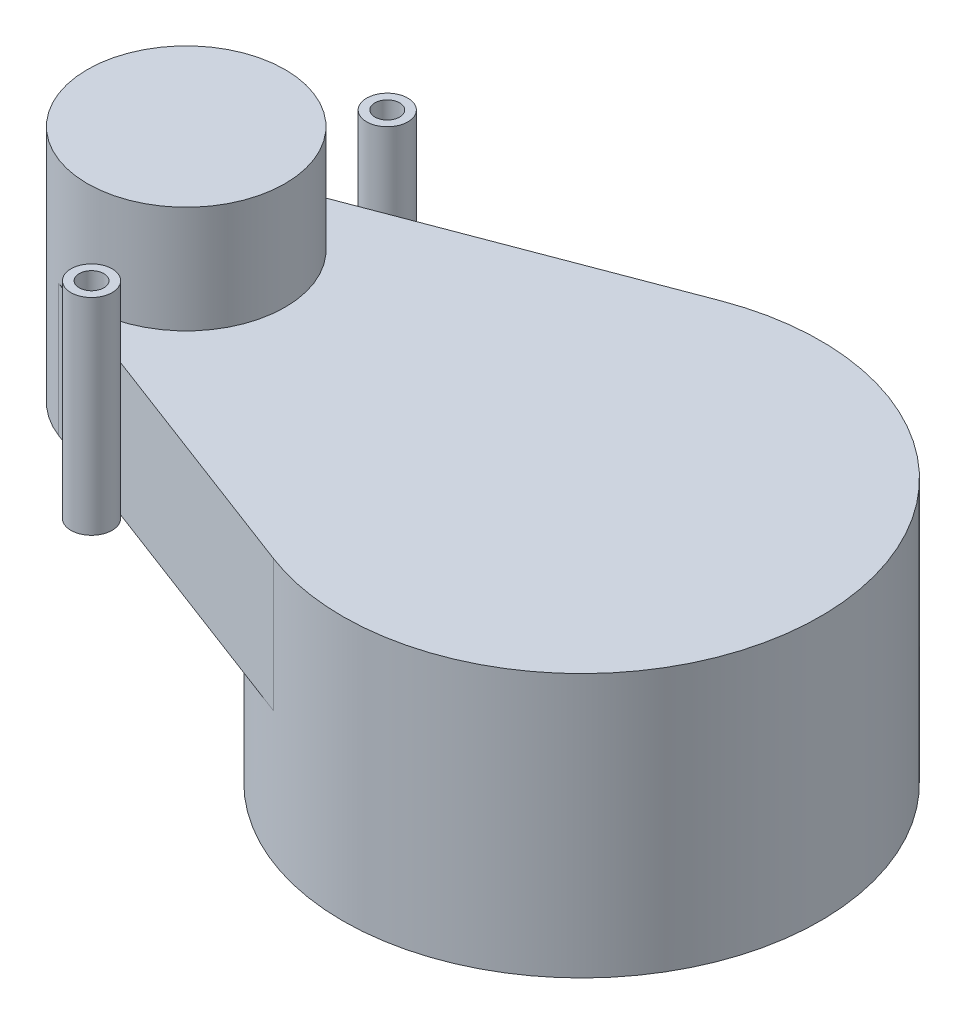
SolidWorks part; units mm, degrees
ref_plane "前视基准面" through (0, 0, 0) normal (0, 0, 1) x (1, 0, 0)
ref_plane "上视基准面" through (0, 0, 0) normal (0, 1, 0) x (1, 0, 0)
ref_plane "右视基准面" through (0, 0, 0) normal (1, 0, 0) x (0, 0, -1)
other "Configuration Table"
sketch "草图1" plane through (0, 0, 0) normal (0, 1, 0) x (1, 0, 0)
  circle A0 centre (0, 0) radius 29
  dimension "D1" = 58
extrude "凸台-拉伸1" add sketch "草图1" against normal blind 16 contours A0
sketch "草图2" plane through (0, 0, 0) normal (0, 1, 0) x (1, 0, 0)
  line L0 (-10.2708, 27.1203) -> (-52.25, 11.2222)
  line L1 (-10.2708, -27.1203) -> (-52.25, -11.2222)
  line L2 (-117.9064, 0) -> (30.9422, 0) construction
  circle A1 centre (0, 0) radius 29
  arc A2 (-10.2708, -27.1203) -> (-10.2708, 27.1203) centre (0, 0) ccw
  arc A3 (-52.25, 11.2222) -> (-52.25, -11.2222) centre (-48, 0) ccw
  circle A4 centre (0, 0) radius 29 construction
  dimension "D2" = 12
  dimension "D3" = 48
  dimension "D1" = 0
extrude "凸台-拉伸2" add sketch "草图2" along normal blind 16
sketch "草图3" plane through (0, 16, 0) normal (0, 1, 0) x (1, 0, 0)
  line L2 (-10.2708, 27.1203) -> (-52.25, 11.2222)
  line L3 (-52.25, -11.2222) -> (-10.2708, -27.1203)
  line L4 (-10.2708, 27.1203) -> (-52.25, 11.2222)
  line L5 (-52.25, -11.2222) -> (-10.2708, -27.1203)
  circle A0 centre (-48, 0) radius 12
  arc A2 (-10.2708, -27.1203) -> (-10.2708, 27.1203) centre (0, 0) ccw
  arc A3 (-52.25, 11.2222) -> (-52.25, -11.2222) centre (-48, 0) ccw
  arc A4 (-10.2708, -27.1203) -> (-10.2708, 27.1203) centre (0, 0) ccw
  arc A5 (-52.25, 11.2222) -> (-52.25, -11.2222) centre (-48, 0) ccw
  arc M8 (-52.25, 11.2222) -> (-52.25, -11.2222) centre (-48, 0) ccw
  dimension "D2" = 24
  dimension "D1" = 0
extrude "凸台-拉伸3" add sketch "草图3" along normal blind 13 contours A0 M8
sketch "草图4" plane through (0, 16, 0) normal (0, 1, 0) x (1, 0, 0)
  line L0 (-71.0231, 0) -> (44.2498, 0) construction
  line L1 (-10.2708, 27.1203) -> (-52.25, 11.2222) construction
  circle A0 centre (-41.5439, -17.95) radius 1.5
  circle A1 centre (-41.5439, 17.95) radius 1.5
  circle A2 centre (-41.5439, -17.95) radius 2.5
  circle A3 centre (-41.5439, 17.95) radius 2.5
  dimension "D1" = 3
  dimension "D3" = 35.9
  dimension "D2" = 1
extrude "凸台-拉伸4" add sketch "草图4" along normal blind 25 from surface at -16 separate body starting at face at (-37.8802, 0, 0)
